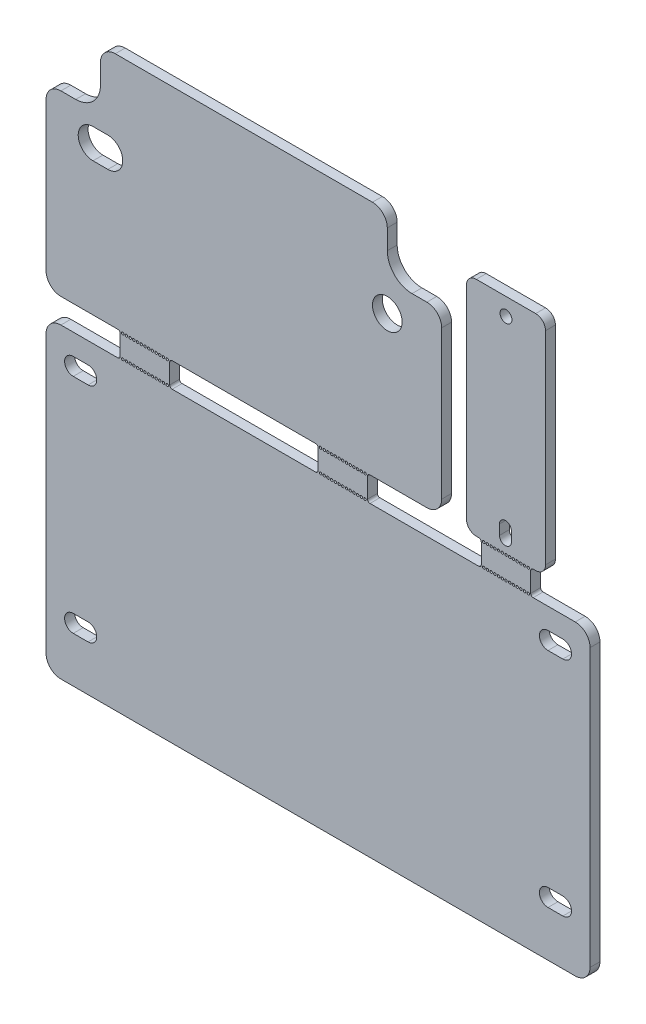
SolidWorks part; units mm, degrees
ref_plane "正面" through (0, 0, 0) normal (0, 0, 1) x (1, 0, 0)
ref_plane "平面" through (0, 0, 0) normal (0, 1, 0) x (1, 0, 0)
ref_plane "右側面" through (0, 0, 0) normal (1, 0, 0) x (0, 0, -1)
sketch "ｽｹｯﾁ1" plane through (0, 0, 0) normal (0, 0, 1) x (1, 0, 0)
  line L0 (-49.5, 24.75) -> (-46.5, 24.75)
  line L1 (55, 32.5) -> (-55, 32.5)
  line L2 (55, 32.5) -> (55, -32.5)
  line L3 (55, -32.5) -> (-55, -32.5)
  line L4 (-55, 32.5) -> (-55, -32.5)
  line L5 (55, 32.5) -> (-55, -32.5) construction
  line L6 (55, -32.5) -> (-55, 32.5) construction
  line L7 (-46.5, 28.25) -> (-49.5, 28.25)
  line L8 (-46.5, 28.25) -> (-46.5, 24.75) construction
  line L10 (-49.5, 28.25) -> (-49.5, 24.75) construction
  line L11 (-46.5, 28.25) -> (-49.5, 24.75) construction
  line L12 (-46.5, 24.75) -> (-49.5, 28.25) construction
  line L13 (-55, 4) -> (55, 4) construction
  line L14 (0, 32.5) -> (0, -32.5) construction
  line L15 (-46.5, -20.25) -> (-49.5, -20.25)
  line L16 (-49.5, -16.75) -> (-46.5, -16.75)
  line L17 (46.5, -20.25) -> (49.5, -20.25)
  line L18 (49.5, -16.75) -> (46.5, -16.75)
  line L19 (46.5, 28.25) -> (49.5, 28.25)
  line L20 (49.5, 24.75) -> (46.5, 24.75)
  arc A2 (-49.5, 28.25) -> (-49.5, 24.75) centre (-49.5, 26.5) ccw
  arc A3 (-46.5, 28.25) -> (-46.5, 24.75) centre (-46.5, 26.5) cw
  arc A4 (-49.5, -20.25) -> (-49.5, -16.75) centre (-49.5, -18.5) cw
  arc A5 (-46.5, -20.25) -> (-46.5, -16.75) centre (-46.5, -18.5) ccw
  arc A6 (46.5, -20.25) -> (46.5, -16.75) centre (46.5, -18.5) cw
  arc A7 (49.5, -20.25) -> (49.5, -16.75) centre (49.5, -18.5) ccw
  arc A8 (49.5, 28.25) -> (49.5, 24.75) centre (49.5, 26.5) cw
  arc A9 (46.5, 28.25) -> (46.5, 24.75) centre (46.5, 26.5) ccw
  point P0 (0, 0)
  point P6 (-48, 26.5)
  dimension "D3" = 3.5
  dimension "D4" = 3
  dimension "D1" = 65
  dimension "D2" = 110
  dimension "D5" = 6
  dimension "D6" = 7
  dimension "D7" = 22.5
extrude "ﾎﾞｽ - 押し出し1" add sketch "ｽｹｯﾁ1" along normal blind 2
fillet "ﾌｨﾚｯﾄ1" radius 3 2 edges at (55, 32.5, 1) (-55, 32.5, 1)
sketch "ｽｹｯﾁ2" plane through (0, 0, 2) normal (0, 0, 1) x (1, 0, 0)
  line L0 (-45.5, 64.5) -> (-42.5, 64.5)
  line L2 (-55, 85.5) -> (-55, 37.5) construction
  line L3 (-55, 37.5) -> (25, 37.5) construction
  line L4 (25, 85.5) -> (25, 37.5) construction
  line L5 (-55, 85.5) -> (25, 37.5) construction
  line L6 (-55, 37.5) -> (25, 85.5) construction
  line L7 (-45.5, 70.5) -> (-42.5, 70.5)
  line L8 (-45.5, 70.5) -> (-45.5, 64.5) construction
  line L10 (-42.5, 70.5) -> (-42.5, 64.5) construction
  line L11 (-45.5, 70.5) -> (-42.5, 64.5) construction
  line L12 (-45.5, 64.5) -> (-42.5, 70.5) construction
  line L17 (-44, 67.5) -> (14, 67.5) construction
  line L18 (-15, 85.5) -> (-15, 37.5) construction
  line L24 (-55, 85.5) -> (25, 85.5) construction
  line L25 (-55, 37.5) -> (25, 37.5)
  line L26 (25, 37.5) -> (25, 73.5)
  line L27 (25, 73.5) -> (14, 73.5)
  line L28 (14, 73.5) -> (14, 85.5)
  line L29 (14, 85.5) -> (-44, 85.5)
  line L30 (-44, 73.5) -> (-44, 85.5)
  line L31 (-55, 73.5) -> (-44, 73.5)
  line L32 (-55, 37.5) -> (-55, 73.5)
  line L33 (-55, 29.5) -> (-55, -32.5) construction
  line L34 (52, 32.5) -> (-52, 32.5) construction
  arc A0 (-45.5, 70.5) -> (-45.5, 64.5) centre (-45.5, 67.5) ccw
  arc A1 (-42.5, 70.5) -> (-42.5, 64.5) centre (-42.5, 67.5) cw
  circle A2 centre (14, 67.5) radius 3
  point P0 (-15, 61.5)
  point P5 (-44, 67.5)
  dimension "D6" = 6
  dimension "D7" = 29
  dimension "D1" = 80
  dimension "D2" = 48
  dimension "D3" = 6
  dimension "D4" = 3
  dimension "D5" = 29
  dimension "D8" = 12
  dimension "D9" = 11
  dimension "D10" = 18
  dimension "D11" = 5
extrude "ﾎﾞｽ - 押し出し2" add sketch "ｽｹｯﾁ2" against normal blind 2 separate body
fillet "ﾌｨﾚｯﾄ5" radius 3 6 edges at (-44, 85.5, 1) (-55, 73.5, 1) (14, 85.5, 1) (25, 73.5, 1) (25, 37.5, 1) (-55, 37.5, 1)
fillet "ﾌｨﾚｯﾄ6" radius 5 2 edges at (14, 73.5, 1) (-44, 73.5, 1)
sketch "ｽｹｯﾁ4" plane through (0, 0, 2) normal (0, 0, 1) x (1, 0, 0)
  line L0 (-40, 37.5) -> (-40, 32.5)
  line L1 (-52, 37.5) -> (22, 37.5) construction
  line L2 (52, 32.5) -> (-52, 32.5) construction
  line L3 (-40, 32.5) -> (-30, 32.5)
  line L4 (-30, 32.5) -> (-30, 37.5)
  line L5 (-30, 37.5) -> (-40, 37.5)
  line L6 (0, 37.5) -> (0, 32.5)
  line L7 (0, 32.5) -> (10, 32.5)
  line L8 (10, 32.5) -> (10, 37.5)
  line L9 (10, 37.5) -> (0, 37.5)
  line L10 (-55, 70.5) -> (-55, 40.5) construction
  line L11 (25, 40.5) -> (25, 70.5) construction
  dimension "D1" = 10
  dimension "D2" = 10
  dimension "D3" = 15
  dimension "D4" = 15
extrude "ﾎﾞｽ - 押し出し4" add sketch "ｽｹｯﾁ4" against normal blind 2
fillet "ﾌｨﾚｯﾄ7" radius 0.5 8 edges at (10, 37.5, 1) (10, 32.5, 1) (0, 37.5, 1) (0, 32.5, 1) (-30, 37.5, 1) (-30, 32.5, 1) (-40, 37.5, 1) (-40, 32.5, 1)
sketch "ｽｹｯﾁ5" plane through (0, 0, 2) normal (0, 0, 1) x (1, 0, 0)
  line L0 (36.6832, 42) -> (36.6832, 40)
  line L1 (30, 82.5) -> (46, 82.5)
  line L2 (30, 82.5) -> (30, 37.5)
  line L3 (30, 37.5) -> (46, 37.5)
  line L4 (46, 82.5) -> (46, 37.5)
  line L5 (30, 82.5) -> (46, 37.5) construction
  line L6 (30, 37.5) -> (46, 82.5) construction
  line L7 (39.0832, 42) -> (36.6832, 42) construction
  line L8 (39.0832, 42) -> (39.0832, 40)
  line L9 (39.0832, 40) -> (36.6832, 40) construction
  line L11 (39.0832, 42) -> (36.6832, 40) construction
  line L12 (39.0832, 40) -> (36.6832, 42) construction
  line L13 (25, 40.5) -> (25, 70.5) construction
  line L14 (52, 32.5) -> (10.5, 32.5) construction
  circle A0 centre (38, 79) radius 1.2
  arc A1 (36.6832, 42) -> (39.0832, 42) centre (37.8832, 42) cw
  arc A2 (39.0832, 40) -> (36.6832, 40) centre (37.8832, 40) cw
  point P0 (38, 60)
  point P7 (37.8832, 41)
  dimension "D3" = 2.4
  dimension "D1" = 45
  dimension "D2" = 16
  dimension "D4" = 2.4
  dimension "D5" = 2
  dimension "D6" = 19
  dimension "D7" = 19
  dimension "D8" = 5
  dimension "D9" = 5
extrude "ﾎﾞｽ - 押し出し5" add sketch "ｽｹｯﾁ5" against normal blind 2 separate body
sketch "ｽｹｯﾁ6" plane through (0, 0, 2) normal (0, 0, 1) x (1, 0, 0)
  line L0 (33, 37.5) -> (33, 32.5)
  line L1 (30, 37.5) -> (46, 37.5) construction
  line L2 (52, 32.5) -> (10.5, 32.5) construction
  line L3 (33, 32.5) -> (43, 32.5)
  line L4 (43, 32.5) -> (43, 37.5)
  line L5 (43, 37.5) -> (33, 37.5)
  line L6 (25, 65.5) -> (30, 65.5)
  line L7 (25, 40.5) -> (25, 70.5) construction
  line L8 (30, 82.5) -> (30, 37.5) construction
  line L9 (30, 65.5) -> (30, 55.5)
  line L10 (30, 55.5) -> (25, 55.5)
  line L11 (25, 55.5) -> (25, 65.5)
  line L13 (10.5, 37.5) -> (22, 37.5) construction
  dimension "D1" = 10
  dimension "D2" = 10
  dimension "D3" = 3
  dimension "D4" = 18
extrude "ﾎﾞｽ - 押し出し6" add sketch "ｽｹｯﾁ6" against normal blind 2
fillet "ﾌｨﾚｯﾄ8" radius 0.5 8 edges at (43, 32.5, 1) (43, 37.5, 1) (33, 32.5, 1) (33, 37.5, 1) (30, 55.5, 1) (25, 55.5, 1) (25, 65.5, 1) (30, 65.5, 1)
fillet "ﾌｨﾚｯﾄ9" radius 2 4 edges at (46, 82.5, 1) (30, 82.5, 1) (46, 37.5, 1) (30, 37.5, 1)
sketch "ｽｹｯﾁ7" plane through (0, 0, 2) normal (0, 0, 1) x (1, 0, 0)
  line L0 (-55, -32.5) -> (55, -32.5)
  line L1 (55, -32.5) -> (55, -29.5)
  line L2 (55, -32.5) -> (55, 29.5) construction
  line L3 (55, -29.5) -> (-55, -29.5)
  line L4 (-55, 29.5) -> (-55, -32.5) construction
  line L5 (-55, -29.5) -> (-55, -32.5)
  dimension "D1" = 3
extrude "ｶｯﾄ - 押し出し1" cut sketch "ｽｹｯﾁ7" against normal blind 10
fillet "ﾌｨﾚｯﾄ10" radius 3 2 edges at (55, -29.5, 1) (-55, -29.5, 1)
sketch "ｽｹｯﾁ8" plane through (0, 0, 2) normal (0, 0, 1) x (1, 0, 0)
  line L0 (-40.5, 37.5) -> (-29.5, 37.5) construction
  line L1 (-40, 37.25) -> (-30, 37.25) construction
  line L2 (-40, 37) -> (-40, 33) construction
  line L3 (-30, 33) -> (-30, 37) construction
  line L4 (-40, 35) -> (-30, 35) construction
  line L5 (-15, 37.5) -> (-15, 32.5) construction
  line L6 (-29.5, 37.5) -> (-0.5, 37.5) construction
  line L7 (-0.5, 32.5) -> (-29.5, 32.5) construction
  line L8 (21.5, 32.5) -> (21.5, 37.5) construction
  line L9 (32.5, 32.5) -> (10.5, 32.5) construction
  line L10 (10.5, 37.5) -> (22, 37.5) construction
  circle A0 centre (-39.5, 37.25) radius 0.25
  circle A1 centre (-38.75, 37.25) radius 0.25
  circle A2 centre (-38, 37.25) radius 0.25
  circle A3 centre (-37.25, 37.25) radius 0.25
  circle A4 centre (-36.5, 37.25) radius 0.25
  circle A5 centre (-35.75, 37.25) radius 0.25
  circle A6 centre (-35, 37.25) radius 0.25
  circle A7 centre (-34.25, 37.25) radius 0.25
  circle A8 centre (-33.5, 37.25) radius 0.25
  circle A9 centre (-32.75, 37.25) radius 0.25
  circle A10 centre (-32, 37.25) radius 0.25
  circle A11 centre (-31.25, 37.25) radius 0.25
  circle A12 centre (-30.5, 37.25) radius 0.25
  circle A13 centre (-30.5, 32.75) radius 0.25
  circle A14 centre (-31.25, 32.75) radius 0.25
  circle A15 centre (-32, 32.75) radius 0.25
  circle A16 centre (-32.75, 32.75) radius 0.25
  circle A17 centre (-33.5, 32.75) radius 0.25
  circle A18 centre (-34.25, 32.75) radius 0.25
  circle A19 centre (-35, 32.75) radius 0.25
  circle A20 centre (-35.75, 32.75) radius 0.25
  circle A21 centre (-36.5, 32.75) radius 0.25
  circle A22 centre (-37.25, 32.75) radius 0.25
  circle A23 centre (-38, 32.75) radius 0.25
  circle A24 centre (-38.75, 32.75) radius 0.25
  circle A25 centre (-39.5, 32.75) radius 0.25
  circle A26 centre (0.5, 32.75) radius 0.25
  circle A27 centre (1.25, 32.75) radius 0.25
  circle A28 centre (2, 32.75) radius 0.25
  circle A29 centre (2.75, 32.75) radius 0.25
  circle A30 centre (3.5, 32.75) radius 0.25
  circle A31 centre (4.25, 32.75) radius 0.25
  circle A32 centre (5, 32.75) radius 0.25
  circle A33 centre (5.75, 32.75) radius 0.25
  circle A34 centre (6.5, 32.75) radius 0.25
  circle A35 centre (7.25, 32.75) radius 0.25
  circle A36 centre (8, 32.75) radius 0.25
  circle A37 centre (8.75, 32.75) radius 0.25
  circle A38 centre (9.5, 32.75) radius 0.25
  circle A39 centre (0.5, 37.25) radius 0.25
  circle A40 centre (1.25, 37.25) radius 0.25
  circle A41 centre (2, 37.25) radius 0.25
  circle A42 centre (2.75, 37.25) radius 0.25
  circle A43 centre (3.5, 37.25) radius 0.25
  circle A44 centre (4.25, 37.25) radius 0.25
  circle A45 centre (5, 37.25) radius 0.25
  circle A46 centre (5.75, 37.25) radius 0.25
  circle A47 centre (6.5, 37.25) radius 0.25
  circle A48 centre (7.25, 37.25) radius 0.25
  circle A49 centre (8, 37.25) radius 0.25
  circle A50 centre (8.75, 37.25) radius 0.25
  circle A51 centre (9.5, 37.25) radius 0.25
  circle A52 centre (33.5, 32.75) radius 0.25
  circle A53 centre (34.25, 32.75) radius 0.25
  circle A54 centre (35, 32.75) radius 0.25
  circle A55 centre (35.75, 32.75) radius 0.25
  circle A56 centre (36.5, 32.75) radius 0.25
  circle A57 centre (37.25, 32.75) radius 0.25
  circle A58 centre (38, 32.75) radius 0.25
  circle A59 centre (38.75, 32.75) radius 0.25
  circle A60 centre (39.5, 32.75) radius 0.25
  circle A61 centre (40.25, 32.75) radius 0.25
  circle A62 centre (41, 32.75) radius 0.25
  circle A63 centre (41.75, 32.75) radius 0.25
  circle A64 centre (42.5, 32.75) radius 0.25
  circle A65 centre (33.5, 37.25) radius 0.25
  circle A66 centre (34.25, 37.25) radius 0.25
  circle A67 centre (35, 37.25) radius 0.25
  circle A68 centre (35.75, 37.25) radius 0.25
  circle A69 centre (36.5, 37.25) radius 0.25
  circle A70 centre (37.25, 37.25) radius 0.25
  circle A71 centre (38, 37.25) radius 0.25
  circle A72 centre (38.75, 37.25) radius 0.25
  circle A73 centre (39.5, 37.25) radius 0.25
  circle A74 centre (40.25, 37.25) radius 0.25
  circle A75 centre (41, 37.25) radius 0.25
  circle A76 centre (41.75, 37.25) radius 0.25
  circle A77 centre (42.5, 37.25) radius 0.25
  dimension "D2" = 0.5
  dimension "D3" = 0.5
  dimension "D1" = 0.25
  dimension "D4" = 13
extrude "ｶｯﾄ - 押し出し2" cut sketch "ｽｹｯﾁ8" against normal blind 10
sketch "ｽｹｯﾁ10" plane through (0, 0, 2) normal (0, 0, 1) x (1, 0, 0)
  line L1 (30, 70.4209) -> (25, 70.4209)
  line L2 (30, 70.4209) -> (30, 50.5791)
  line L3 (30, 50.5791) -> (25, 50.5791)
  line L4 (25, 70.4209) -> (25, 50.5791)
  line L5 (30, 70.4209) -> (25, 50.5791) construction
  line L6 (30, 50.5791) -> (25, 70.4209) construction
  line L7 (25, 40.5) -> (25, 55) construction
  point P0 (27.5, 60.5)
  dimension "D1" = 5
extrude "ｶｯﾄ - 押し出し3" cut sketch "ｽｹｯﾁ10" against normal blind 10
